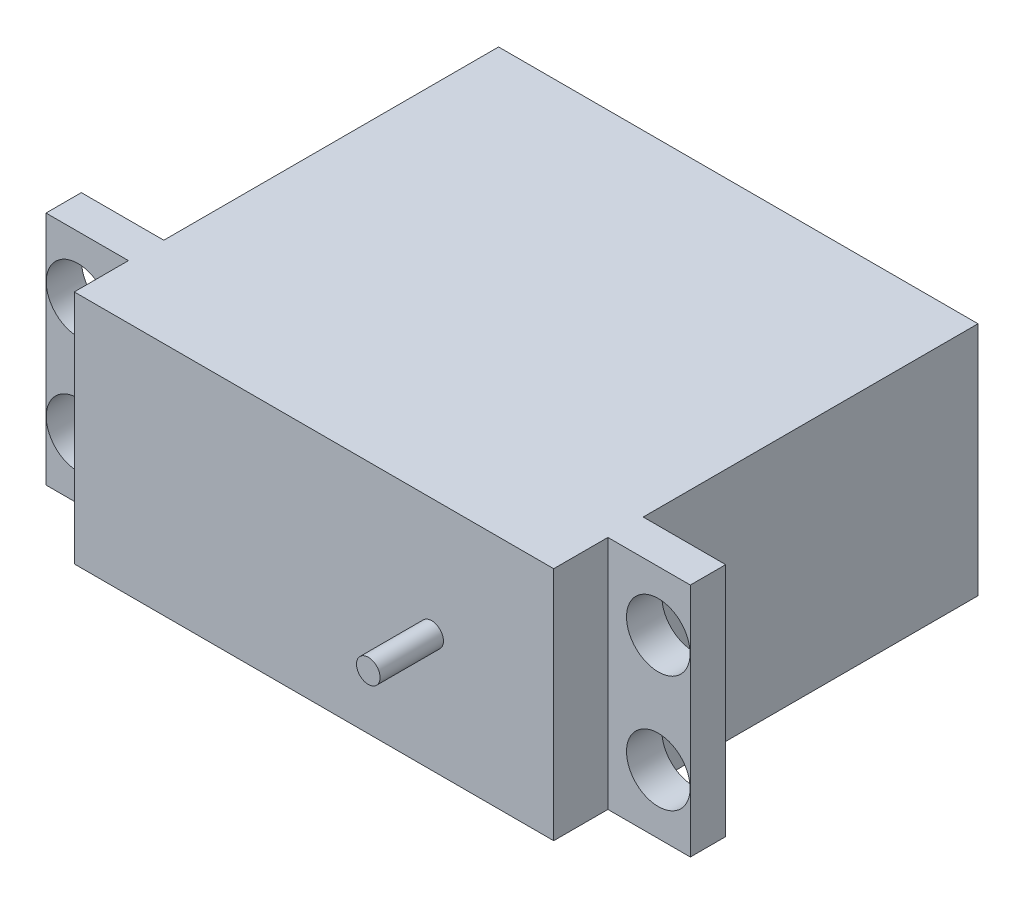
SolidWorks part; units mm, degrees
ref_plane "Front Plane" through (0, 0, 0) normal (0, 0, 1) x (1, 0, 0)
ref_plane "Top Plane" through (0, 0, 0) normal (0, 1, 0) x (1, 0, 0)
ref_plane "Right Plane" through (0, 0, 0) normal (1, 0, 0) x (0, 0, -1)
sketch "Sketch1" plane through (0, 0, 0) normal (0, 0, 1) x (1, 0, 0)
  line L1 (0, 0) -> (40.7, 0)
  line L2 (0, 0) -> (0, 20)
  line L3 (0, 20) -> (40.7, 20)
  line L4 (40.7, 0) -> (40.7, 20)
extrude "Boss-Extrude1" add sketch "Sketch1" along normal blind 36.02
sketch "Sketch3" plane through (0, 0, 36.02) normal (0, 0, 1) x (1, 0, 0)
  circle A0 centre (30.34, 10) radius 1
extrude "Boss-Extrude2" add sketch "Sketch3" along normal blind 5.38
sketch "Sketch4" plane through (40.7, 0, 0) normal (1, 0, 0) x (0, 0, -1)
  line L2 (-36.02, 20) -> (0, 20) construction
  line L3 (-28.42, 20) -> (-31.42, 20)
  line L4 (-28.42, 20) -> (-28.42, 0)
  line L5 (-28.42, 0) -> (-31.42, 0)
  line L6 (-31.42, 20) -> (-31.42, 0)
  line L7 (-36.02, 0) -> (0, 0) construction
extrude "Boss-Extrude3" add sketch "Sketch4" along normal blind 7
sketch "Sketch6" plane through (0, 0, 0) normal (-1, 0, 0) x (0, 0, 1)
  line L1 (36.02, 20) -> (0, 20) construction
  line L2 (36.02, 0) -> (0, 0) construction
  line L3 (28.42, 20) -> (31.42, 20)
  line L4 (28.42, 20) -> (28.42, 0)
  line L5 (28.42, 0) -> (31.42, 0)
  line L6 (31.42, 20) -> (31.42, 0)
extrude "Boss-Extrude4" add sketch "Sketch6" along normal blind 7
sketch "Sketch7" plane through (0, 0, 31.42) normal (0, 0, 1) x (1, 0, 0)
  circle A0 centre (-4.28, 14.95) radius 2.7
  circle A1 centre (-4.28, 5.05) radius 2.7
  circle A2 centre (44.98, 14.95) radius 2.7
  circle A3 centre (44.98, 5.05) radius 2.7
extrude "Cut-Extrude1" cut sketch "Sketch7" against normal blind 3
